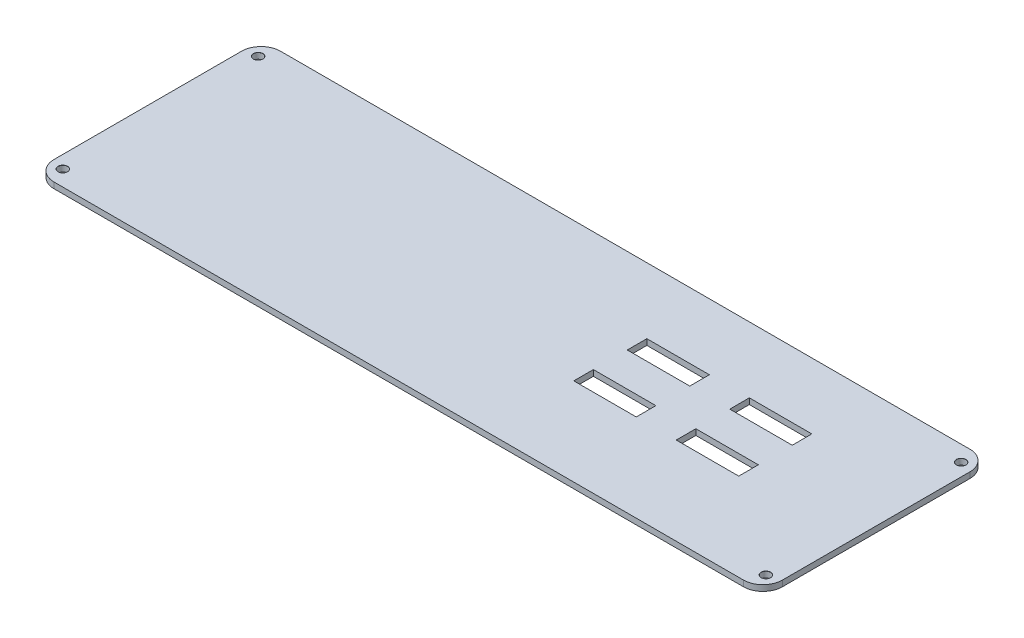
SolidWorks part; units mm, degrees
ref_plane "Front Plane" through (0, 0, 0) normal (0, 0, 1) x (1, 0, 0)
ref_plane "Top Plane" through (0, 0, 0) normal (0, 1, 0) x (1, 0, 0)
ref_plane "Right Plane" through (0, 0, 0) normal (1, 0, 0) x (0, 0, -1)
sketch "Sketch1" plane through (0, 0, 0) normal (0, 1, 0) x (1, 0, 0)
  line L1 (93.25, -29) -> (-93.25, -29)
  line L2 (93.25, -29) -> (93.25, 29)
  line L3 (93.25, 29) -> (-93.25, 29)
  line L4 (-93.25, -29) -> (-93.25, 29)
  line L5 (93.25, -29) -> (-93.25, 29) construction
  line L6 (93.25, 29) -> (-93.25, -29) construction
  point P0 (0, 0)
  dimension "D1" = 58
  dimension "D2" = 186.5
extrude "Boss-Extrude1" add sketch "Sketch1" along normal blind 1.5
fillet "Fillet1" radius 5 4 edges at (-93.25, 0.75, -29) (93.25, 0.75, -29) (93.25, 0.75, 29) (-93.25, 0.75, 29)
hole_wizard "M2 Clearance Hole1" positions "Sketch2" profile "Sketch3" hole size "M2" standard "ANSI Metric" end condition up to next
sketch "Sketch2" plane through (0, 1.5, 0) normal (0, 1, 0) x (1, 0, 0)
  line L0 (-90, -25) -> (-90, 25) construction
  line L1 (-90, 25) -> (90, 25) construction
  line L2 (90, 25) -> (-90, -25) construction
  line L6 (90, 25) -> (90, -25) construction
  line L7 (90, -25) -> (-90, -25) construction
  point P0 (-90, 25)
  point P2 (90, 25)
  point P4 (90, -25)
  point P6 (-90, -25)
  point P16 (0, 0)
  dimension "D1" = 180
  dimension "D2" = 50
sketch "Sketch3" plane through (-90, 1.5, -25) normal (1, 0, 0) x (0, 0, 1)
  line L0 (0, 0) -> (0, 1.5)
  line L1 (0, 1.5) -> (1.2, 1.5)
  line L2 (1.2, 1.5) -> (1.2, 0.025)
  line L3 (1.2, 0.025) -> (1.225, 0)
  line L5 (1.225, 0) -> (0, 0)
  line L6 (-1.2, 0.025) -> (-1.225, 0) construction
  line L11 (0, -6.35) -> (0, 107.95) construction
  dimension "Thru Hole Dia." = 2.4
  dimension "Thru Hole Depth" = 1.5
  dimension "Near C'Sink Dia." = 2.45
  dimension "Near C'Sink Angle" = 90
sketch "Sketch4" plane through (0, 1.5, 0) normal (0, 1, 0) x (1, 0, 0)
  line L1 (22.3766, 12.1528) -> (38.3766, 12.1528)
  line L2 (22.3766, 12.1528) -> (22.3766, 7.1374)
  line L3 (22.3766, 7.1374) -> (38.3766, 7.1374)
  line L4 (38.3766, 12.1528) -> (38.3766, 7.1374)
  line L5 (48.6113, 12.1528) -> (64.6113, 12.1528)
  line L6 (48.6113, 12.1528) -> (48.6113, 7.1374)
  line L7 (48.6113, 7.1374) -> (64.6113, 7.1374)
  line L8 (64.6113, 12.1528) -> (64.6113, 7.1374)
  line L9 (22.3766, -1.5432) -> (38.3766, -1.5432)
  line L10 (22.3766, -1.5432) -> (22.3766, -6.5587)
  line L11 (22.3766, -6.5587) -> (38.3766, -6.5587)
  line L12 (38.3766, -1.5432) -> (38.3766, -6.5587)
  line L13 (48.6113, -1.5432) -> (64.6113, -1.5432)
  line L14 (48.6113, -1.5432) -> (48.6113, -6.5587)
  line L15 (48.6113, -6.5587) -> (64.6113, -6.5587)
  line L16 (64.6113, -1.5432) -> (64.6113, -6.5587)
  dimension "D1" = 16
extrude "Cut-Extrude1" cut sketch "Sketch4" against normal through all
